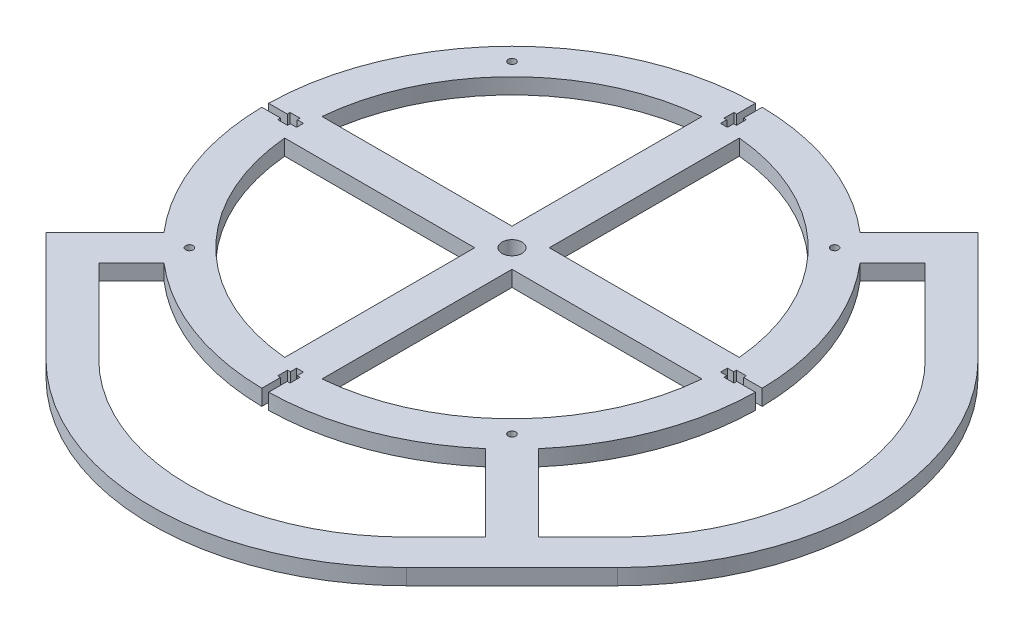
SolidWorks part; units mm, degrees
ref_plane "Front Plane" through (0, 0, 0) normal (0, 0, 1) x (1, 0, 0)
ref_plane "Top Plane" through (0, 0, 0) normal (0, 1, 0) x (1, 0, 0)
ref_plane "Right Plane" through (0, 0, 0) normal (1, 0, 0) x (0, 0, -1)
sketch "Sketch1" plane through (0, 0, 0) normal (0, 1, 0) x (1, 0, 0)
  line L0 (0, -99.238) -> (0, 99.238) construction
  line L1 (-99.238, 0) -> (99.238, 0) construction
  line L2 (-98.9542, -7.5) -> (98.9542, -7.5)
  line L3 (7.5, -98.9542) -> (7.5, 98.9542)
  line L4 (-98.9542, 7.5) -> (98.9542, 7.5)
  line L5 (-7.5, -98.9542) -> (-7.5, 98.9542)
  line L6 (-7.5, -99.238) -> (-7.5, 99.238) construction
  line L7 (7.5, -99.238) -> (7.5, 99.238) construction
  line L8 (-99.238, -7.5) -> (99.238, -7.5) construction
  line L9 (-99.238, 7.5) -> (99.238, 7.5) construction
  line L10 (-88.3883, -88.3883) -> (17.6777, -194.4544) construction
  line L11 (17.6777, -194.4544) -> (194.4544, -17.6777) construction
  line L12 (194.4544, -17.6777) -> (88.3883, 88.3883) construction
  line L13 (0, 0) -> (33755.9757, 33755.9757) construction
  line L14 (-88.3883, -88.3883) -> (-70.1719, -70.1719) construction
  line L15 (88.3883, 88.3883) -> (70.1719, 70.1719) construction
  line L16 (106.066, -106.066) -> (70.1719, -70.1719) construction
  line L17 (111.3693, -100.7627) -> (75.2745, -64.6679)
  line L18 (88.3883, 77.7817) -> (75.2745, 64.6679) construction
  line L19 (183.8478, -17.6777) -> (88.3883, 77.7817) construction
  line L20 (17.6777, -183.8478) -> (183.8478, -17.6777) construction
  line L21 (-77.7817, -88.3883) -> (17.6777, -183.8478) construction
  line L22 (-77.7817, -88.3883) -> (-64.6679, -75.2745) construction
  line L23 (100.7627, -111.3693) -> (64.6679, -75.2745)
  line L24 (88.3883, 98.9949) -> (64.6679, 75.2745)
  line L25 (205.061, -17.6777) -> (88.3883, 98.9949) construction
  line L26 (17.6777, -205.061) -> (205.061, -17.6777) construction
  line L27 (-98.9949, -88.3883) -> (17.6777, -205.061) construction
  line L28 (-98.9949, -88.3883) -> (-75.2745, -64.6679)
  line L29 (-77.7817, -88.3883) -> (-64.8686, -75.4752) construction
  line L30 (-98.9949, -88.3883) -> (-75.4752, -64.8686) construction
  line L31 (88.3883, 77.7817) -> (75.4752, 64.8686) construction
  line L32 (88.3883, 98.9949) -> (64.8686, 75.4752) construction
  line L33 (111.3693, -100.7627) -> (75.4752, -64.8686) construction
  line L34 (100.7627, -111.3693) -> (64.8686, -75.4752) construction
  line L35 (90.1561, -132.5825) -> (132.5825, -90.1561)
  line L36 (-98.9949, -88.3883) -> (-54.8008, -132.5825)
  line L37 (88.3883, 98.9949) -> (132.5825, 54.8008)
  line L38 (-54.8008, -132.5825) -> (132.5825, 54.8008) construction
  line L39 (-77.7817, -88.3883) -> (-64.6679, -75.2745)
  line L40 (-77.7817, -88.3883) -> (-44.1942, -121.9759)
  line L41 (79.5495, -121.9759) -> (121.9759, -79.5495)
  line L42 (88.3883, 77.7817) -> (121.9759, 44.1942)
  line L43 (88.3883, 77.7817) -> (75.2745, 64.6679)
  line L44 (-75.2745, -64.6679) -> (-64.6679, -75.2745)
  line L45 (64.6679, 75.2745) -> (75.2745, 64.6679)
  circle A0 centre (0, 0) radius 100 construction
  circle A1 centre (0, 0) radius 99.238
  circle A2 centre (0, 0) radius 84.238
  circle A3 centre (0, 0) radius 157.5 construction
  circle A5 centre (0, 0) radius 132.7121 construction
  arc A6 (90.1561, -132.5825) -> (-54.8008, -132.5825) centre (17.6777, -60.1041) cw
  arc A7 (132.5825, -90.1561) -> (132.5825, 54.8008) centre (60.1041, -17.6777) ccw
  arc A8 (79.5495, -121.9759) -> (-44.1942, -121.9759) centre (17.6777, -60.1041) cw
  arc A9 (121.9759, -79.5495) -> (121.9759, 44.1942) centre (60.1041, -17.6777) ccw
  point P7 (0, 0)
  point P11 (0, 0)
  point P65 (111.3693, -111.3693)
  dimension "D1" = 200
  dimension "D2" = 0.762
  dimension "D3" = 15
  dimension "D6" = 25
  dimension "D7" = 25
  dimension "D8" = 50
  dimension "D9" = 15
  dimension "D10" = 45
  dimension "D13" = 60
  dimension "D4" = 7.5
  dimension "D5" = 7.5
  dimension "D11" = 7.5
  dimension "D12" = 7.5
  dimension "D14" = 15
extrude "Boss-Extrude1" add sketch "Sketch1" along normal mid plane 6.35
sketch "Sketch2" plane through (0, 0, 0) normal (0, 1, 0) x (1, 0, 0)
  line L0 (-1.375, 85.238) -> (-1.375, 99.238)
  line L1 (-1.375, 85.238) -> (1.375, 85.238)
  line L2 (-1.375, 99.238) -> (1.375, 99.238)
  line L3 (1.375, 85.238) -> (1.375, 99.238)
  line L4 (-1.375, 85.238) -> (1.375, 99.238) construction
  line L5 (-1.375, 99.238) -> (1.375, 85.238) construction
  line L6 (-2.5, 87.738) -> (-2.5, 91.738)
  line L7 (-2.5, 87.738) -> (2.5, 87.738)
  line L8 (-2.5, 91.738) -> (2.5, 91.738)
  line L9 (2.5, 87.738) -> (2.5, 91.738)
  line L10 (-2.5, 87.738) -> (2.5, 91.738) construction
  line L11 (-2.5, 91.738) -> (2.5, 87.738) construction
  line L12 (0, -1000) -> (0, 49000) construction
  line L13 (-1000, 0) -> (49000, 0) construction
  circle A0 centre (0, 0) radius 99.238 construction
  point P1 (0, 92.238)
  point P2 (0, 89.738)
  dimension "D1" = 2.75
  dimension "D2" = 14
  dimension "D3" = 4
  dimension "D4" = 5
  dimension "D5" = 2.5
extrude "Cut-Extrude1" cut sketch "Sketch2" against normal through all both and the other way through all contours L7 L0 L1 L3 | L8 L0 L7 L3 | L7 L9 L8 L3 | L0 L8 L3 L2 | L8 L6 L7 L0
pattern_circular "CirPattern1" count 4 over 360 about axis through (0, 0, 0) along (0, 1, 0) of "Cut-Extrude1"
hole_wizard "Ø3.0 (3) Diameter Hole1" positions "Sketch3" profile "Sketch4" hole size "Ø3.0" standard "ANSI Metric" end condition up to next
sketch "Sketch3" plane through (0, 3.175, 0) normal (0, 1, 0) x (1, 0, 0)
  line L0 (-70.1719, -70.1719) -> (70.1719, 70.1719) construction
  line L2 (-70.1719, 70.1719) -> (70.1719, -70.1719) construction
  line L4 (70.1719, 70.1719) -> (59.5653, 59.5653)
  line L6 (70.1719, -70.1719) -> (59.5653, -59.5653)
  line L8 (-70.1719, -70.1719) -> (-59.5653, -59.5653)
  line L10 (-70.1719, 70.1719) -> (-59.5653, 59.5653)
  arc A2 (83.9035, 7.5) -> (7.5, 83.9035) centre (0, 0) ccw construction
  arc A3 (7.5, -83.9035) -> (83.9035, -7.5) centre (0, 0) ccw construction
  arc A4 (-83.9035, -7.5) -> (-7.5, -83.9035) centre (0, 0) ccw construction
  arc A5 (-7.5, 83.9035) -> (-83.9035, 7.5) centre (0, 0) ccw construction
  circle A6 centre (0, 0) radius 99.238
  arc A7 (-1.375, 99.2285) -> (-99.2285, 1.375) centre (0, 0) ccw construction
  point P107 (0, 0)
  point P324 (0, 0)
  point P360 (-64.8686, 64.8686)
  point P362 (64.8686, 64.8686)
  point P364 (64.8686, -64.8686)
  point P366 (-64.8686, -64.8686)
sketch "Sketch4" plane through (-64.8686, 3.175, 64.8686) normal (1, 0, 0) x (0, 0, 1)
  line L0 (0, 0) -> (0, 6.35)
  line L1 (0, 6.35) -> (1.5, 6.35)
  line L2 (1.5, 6.35) -> (1.5, 0)
  line L5 (1.5, 0) -> (0, 0)
  line L11 (0, -6.35) -> (0, 107.95) construction
  dimension "Thru Hole Dia." = 3
  dimension "Thru Hole Depth" = 6.35
hole_wizard "Ø8.0 (8) Diameter Hole1" positions "Sketch5" profile "Sketch6" hole size "Ø8.0" standard "ANSI Metric" end condition up to next
sketch "Sketch5" plane through (0, 3.175, 0) normal (0, 1, 0) x (1, 0, 0)
  point P0 (0, 0)
sketch "Sketch6" plane through (0, 3.175, 0) normal (1, 0, 0) x (0, 0, 1)
  line L0 (0, 0) -> (0, 6.35)
  line L1 (0, 6.35) -> (4, 6.35)
  line L2 (4, 6.35) -> (4, 0)
  line L5 (4, 0) -> (0, 0)
  line L11 (0, -6.35) -> (0, 107.95) construction
  dimension "Thru Hole Dia." = 8
  dimension "Thru Hole Depth" = 6.35
